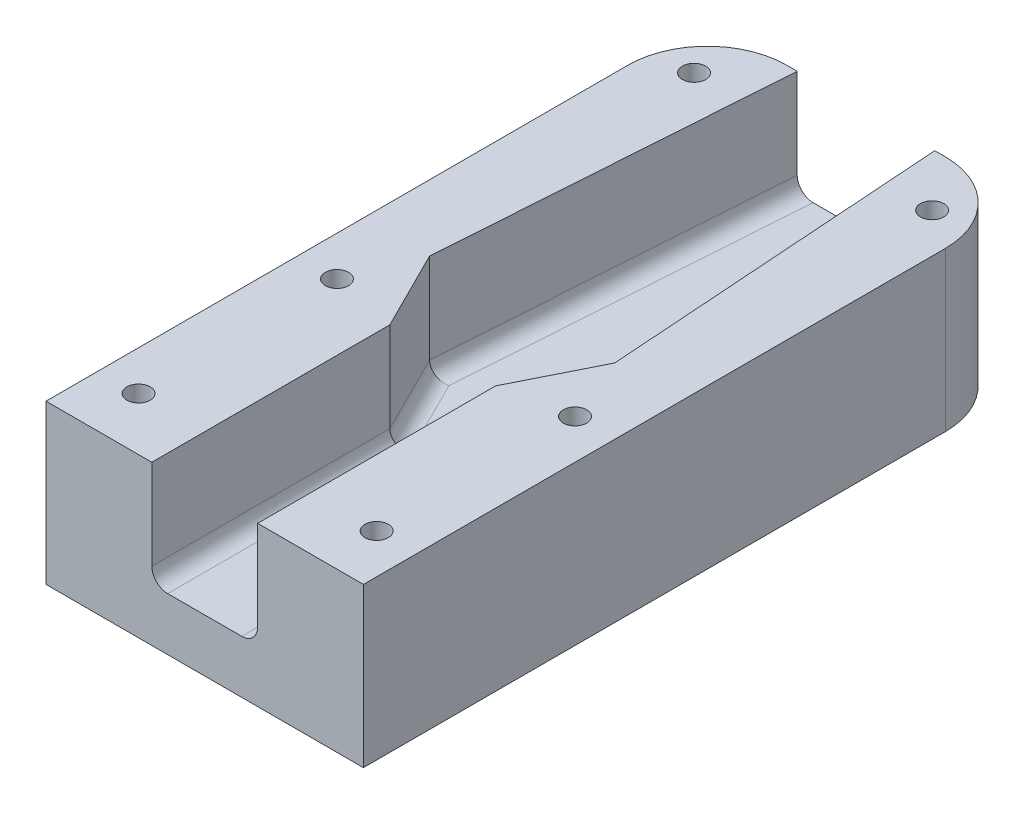
SolidWorks part; units mm, degrees
material "ABS"
ref_plane "Front Plane" through (0, 0, 0) normal (0, 0, 1) x (1, 0, 0)
ref_plane "Top Plane" through (0, 0, 0) normal (0, 1, 0) x (1, 0, 0)
ref_plane "Right Plane" through (0, 0, 0) normal (1, 0, 0) x (0, 0, -1)
sketch "草图1" plane through (0, 0, 0) normal (0, 1, 0) x (1, 0, 0)
  line L1 (-30, 62.5) -> (30, 62.5)
  line L2 (-30, 62.5) -> (-30, -62.5)
  line L3 (-30, -62.5) -> (30, -62.5)
  line L4 (30, 62.5) -> (30, -62.5)
  line L5 (-30, 62.5) -> (30, -62.5) construction
  line L6 (-30, -62.5) -> (30, 62.5) construction
  point P0 (0, 0)
extrude "凸台-拉伸1" add sketch "草图1" along normal blind 30
sketch "草图2" plane through (0, 30, 0) normal (0, 1, 0) x (1, 0, 0)
  line L0 (-30, -62.5) -> (30, 62.5)
  line L2 (22.5, -52.5) -> (-22.5, -52.5)
  line L3 (22.5, -52.5) -> (22.5, 52.5)
  line L4 (22.5, 52.5) -> (-22.5, 52.5)
  line L5 (-22.5, -52.5) -> (-22.5, 52.5)
  line L6 (22.5, -52.5) -> (-22.5, 52.5) construction
  line L7 (22.5, 52.5) -> (-22.5, -52.5) construction
  circle A0 centre (-22.5, 52.5) radius 2.2
  circle A1 centre (-22.5, -52.5) radius 2.2
  circle A2 centre (22.5, -52.5) radius 2.2
  circle A3 centre (22.5, 52.5) radius 2.2
  point P4 (0, 0)
extrude "切除-拉伸1" cut sketch "草图2" against normal through all contours L5 A1 L2 | L2 A1 L5 | L2 A2 L3 | L3 A2 L2 | L4 A0 L5 | L5 A0 L4 | L3 A3 L4 | L4 A3 L3
sketch "草图3" plane through (0, 0, 0) normal (0, -1, 0) x (-1, 0, 0)
  line L2 (30, -15) -> (-30, -15)
  line L3 (30, 62.5) -> (30, -62.5) construction
  line L4 (-30, -62.5) -> (-30, 62.5) construction
  circle A0 centre (0, -15) radius 22.5
  circle A1 centre (-22.5, -15) radius 2.2
  circle A2 centre (22.5, -15) radius 2.2
extrude "切除-拉伸2" cut sketch "草图3" against normal through all contours A0 A1 L2 | L2 A1 A0 | A0 A1 L2 | L2 A1 A0 | L2 A2 A0 | A0 A2 L2 | L2 A2 A0 | A0 A2 L2
sketch "草图4" plane through (0, 30, 0) normal (0, 1, 0) x (1, 0, 0)
  line L0 (0, -62.5) -> (0, 62.5)
  line L1 (-30, -62.5) -> (-10, -62.5)
  line L2 (-30, -62.5) -> (-30, -17.5)
  line L3 (-30, -17.5) -> (-10, -17.5)
  line L4 (-10, -62.5) -> (-10, -17.5)
  line L5 (30, -62.5) -> (10, -62.5)
  line L6 (30, -62.5) -> (30, -17.5)
  line L7 (30, -17.5) -> (10, -17.5)
  line L8 (10, -62.5) -> (10, -17.5)
  line L9 (-30, -62.5) -> (30, -62.5) construction
  line L10 (30, 62.5) -> (-30, 62.5) construction
  line L11 (17.5, -2.5) -> (10, -17.5)
  line L12 (0, 62.5) -> (-13, 62.5)
  line L13 (0, 62.5) -> (0, -2.5)
  line L14 (0, -2.5) -> (-13, -2.5)
  line L15 (-13, 62.5) -> (-13, -2.5)
  line L16 (0, 62.5) -> (-17.5, 62.5)
  line L17 (0, 62.5) -> (0, -2.5)
  line L18 (0, -2.5) -> (-17.5, -2.5)
  line L19 (-17.5, 62.5) -> (-17.5, -2.5)
  line L20 (0, 62.5) -> (13, 62.5)
  line L21 (0, 62.5) -> (0, -2.5)
  line L22 (0, -2.5) -> (13, -2.5)
  line L23 (13, 62.5) -> (13, -2.5)
  line L24 (0, 62.5) -> (17.5, 62.5)
  line L25 (0, 62.5) -> (0, -2.5)
  line L26 (0, -2.5) -> (17.5, -2.5)
  line L27 (17.5, 62.5) -> (17.5, -2.5)
  line L28 (-10, -17.5) -> (-17.5, -2.5)
  line L29 (-13, 62.5) -> (-17.5, -2.5)
  line L30 (13, 62.5) -> (17.5, -2.5)
  line M32 (30, 62.5) -> (-30, 62.5)
  line M34 (-30, -62.5) -> (30, -62.5)
extrude "切除-拉伸3" cut sketch "草图4" against normal blind 20 contours L26 L22 L0 L8 L11 M34 | L28 L4 L0 L14 L18 M34 | L15 L29 L18 | L15 L14 L0 M32 | L23 L0 L22 M32 | L30 L23 L26
fillet "圆角1" radius 3 6 edges at (15.25, 10, -30) (13.75, 10, 10) (10, 10, 40) (-13.75, 10, 10) (-10, 10, 40) (-15.25, 10, -30)
fillet "圆角2" radius 15 2 edges at (-30, 15, -62.5) (30, 15, -62.5)
sketch "草图5" plane through (0, 0, 0) normal (0, -1, 0) x (1, 0, 0)
  circle A0 centre (-22.5, -52.5) radius 3.75
  circle A2 centre (22.5, -52.5) radius 3.75
  circle A3 centre (-22.5, 15) radius 3.75
  circle A4 centre (22.5, 15) radius 3.75
  circle A5 centre (-22.5, 52.5) radius 3.75
  circle A6 centre (22.5, 52.5) radius 3.75
extrude "切除-拉伸4" cut sketch "草图5" against normal blind 20
